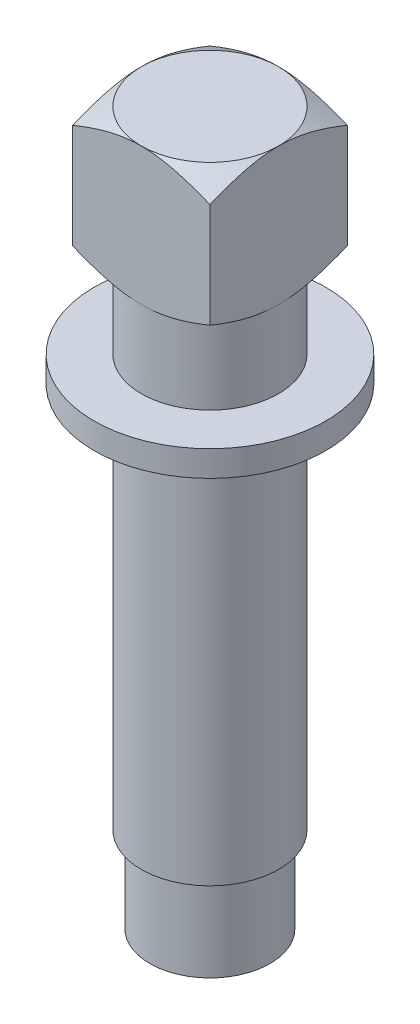
SolidWorks part; units mm, degrees
material "Wrought Stainless Steel"
ref_plane "Front Plane" through (0, 0, 0) normal (0, 0, 1) x (1, 0, 0)
ref_plane "Top Plane" through (0, 0, 0) normal (0, 1, 0) x (1, 0, 0)
ref_plane "Right Plane" through (0, 0, 0) normal (1, 0, 0) x (0, 0, -1)
sketch "Sketch1" plane through (0, 0, 0) normal (0, 0, 1) x (1, 0, 0)
  line L0 (0, 0) -> (-7, 0)
  line L1 (-7, 0) -> (-7, 10)
  line L2 (-7, 10) -> (-8, 10)
  line L3 (-8, 10) -> (-8, 55)
  line L4 (-8, 55) -> (-13.5, 55)
  line L5 (-13.5, 55) -> (-13.5, 58)
  line L6 (-13.5, 58) -> (-8, 58)
  line L8 (-8, 67) -> (0, 67)
  line L9 (0, 67) -> (0, 0)
  line L10 (-8, 58) -> (-8, 67)
  point P12 (-10.75, 55)
  dimension "D1" = 7
  dimension "D2" = 8
  dimension "D3" = 13.5
  dimension "D4" = 10
  dimension "D5" = 45
  dimension "D6" = 3
  dimension "D7" = 9
revolve "Revolve1" add sketch "Sketch1" angle 360 about L9
sketch "Sketch2" plane through (0, 67, 0) normal (0, 1, 0) x (1, 0, 0)
  line L1 (-8, 8) -> (8, 8)
  line L2 (-8, 8) -> (-8, -8)
  line L3 (-8, -8) -> (8, -8)
  line L4 (8, 8) -> (8, -8)
  line L5 (-8, 8) -> (8, -8) construction
  line L6 (-8, -8) -> (8, 8) construction
  point P0 (0, 0)
  dimension "D1" = 16
  dimension "D2" = 16
extrude "Boss-Extrude1" add sketch "Sketch2" along normal blind 16
sketch "Sketch3" plane through (0, 83, 0) normal (0, 1, 0) x (1, 0, 0)
  line L0 (-8, -8) -> (8, -8) construction
  circle A0 centre (0, 0) radius 8
extrude "Cut-Extrude1" cut sketch "Sketch3" against normal blind 10 draft 60 flip side to cut
sketch "Sketch4" plane through (0, 67, 0) normal (0, -1, 0) x (1, 0, 0)
  circle A0 centre (0, 0) radius 8 construction
  circle A1 centre (0, 0) radius 8
extrude "Cut-Extrude2" cut sketch "Sketch4" against normal blind 10 draft 60 flip side to cut
